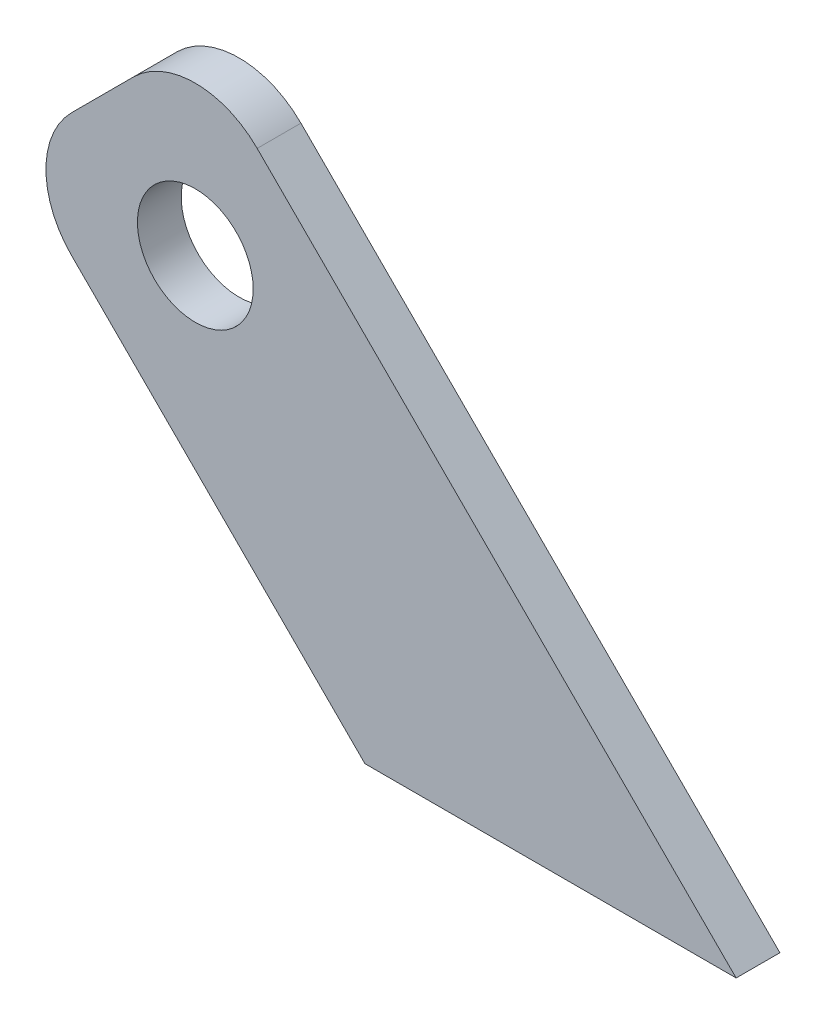
SolidWorks part; units mm, degrees
ref_plane "Front Plane" through (0, 0, 0) normal (0, 0, 1) x (1, 0, 0)
ref_plane "Top Plane" through (0, 0, 0) normal (0, 1, 0) x (1, 0, 0)
ref_plane "Right Plane" through (0, 0, 0) normal (1, 0, 0) x (0, 0, -1)
sketch "Sketch1" plane through (0, 0, 0) normal (0, 0, 1) x (1, 0, 0)
  line L3 (0, 0) -> (38.1, 38.0993) construction
  line L4 (0, 0) -> (76.2, 0) construction
  line L5 (38.1, 38.0993) -> (76.2, 0) construction
  line L6 (29.12, 42.5897) -> (33.6099, 47.0795)
  line L7 (42.5901, 47.0795) -> (89.6705, 0)
  line L8 (89.6705, 0) -> (-13.4705, 0)
  line L9 (8.9803, 0) -> (31.3648, 22.3841)
  line L10 (40.345, 22.3841) -> (62.7295, 0)
  line L11 (-1.1513, 12.319) -> (77.3513, 12.319)
  line L12 (40.345, 22.3841) -> (29.1199, 33.6094)
  circle A0 centre (38.1, 38.0993) radius 4.1999
  arc A1 (31.3648, 22.3841) -> (40.345, 22.3841) centre (35.8549, 17.8939) cw
  arc A2 (42.5901, 47.0795) -> (33.6099, 47.0795) centre (38.1, 42.5894) ccw
  arc A3 (29.1199, 33.6094) -> (29.12, 42.5897) centre (33.61, 38.0995) cw
  point P6 (38.1, 0)
  point P21 (0, 0)
  dimension "D3" = 8.3998
  dimension "D4" = 9.525
  dimension "D7" = 6.35
  dimension "D9" = 6.35
  dimension "D1" = 53.881
  dimension "D2" = 76.2
  dimension "D5" = 9.525
  dimension "D6" = 6.35
  dimension "D8" = 12.319
extrude "Boss-Extrude1" add sketch "Sketch1" along normal blind 3.175 contours A3 L12 L10 L11 L7 A2 L6 A0
